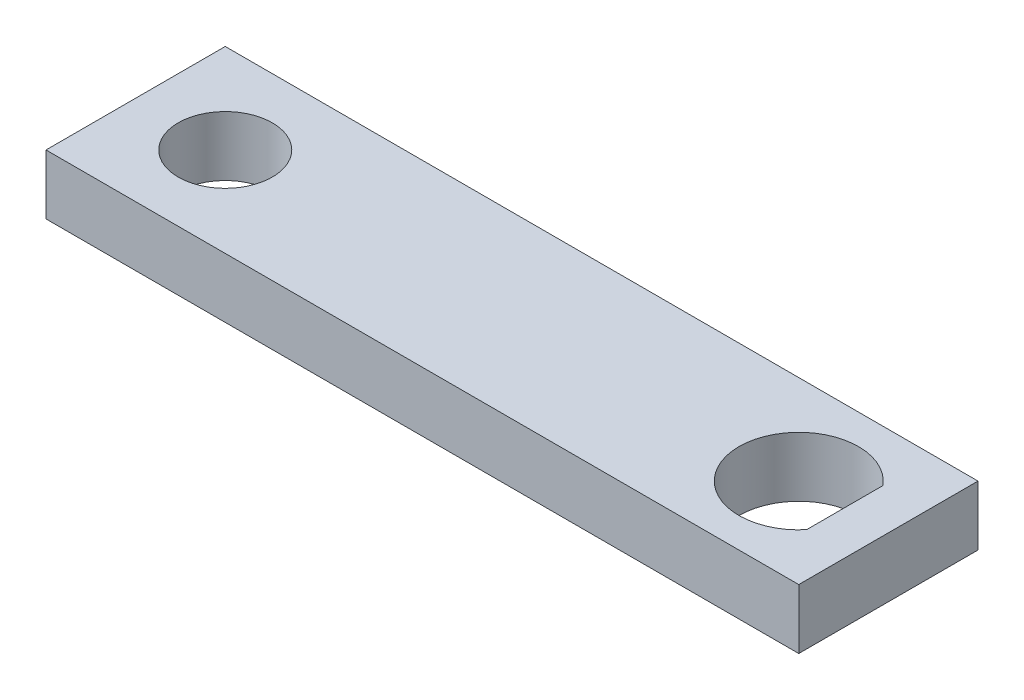
SolidWorks part; units mm, degrees
ref_plane "Front" through (0, 0, 0) normal (0, 0, 1) x (1, 0, 0)
ref_plane "Top" through (0, 0, 0) normal (0, 1, 0) x (-1, 0, 0)
ref_plane "Right" through (0, 0, 0) normal (1, 0, 0) x (0, 0, -1)
sketch "Sketch1" plane through (0, 0, 0) normal (0, 0, 1) x (1, 0, 0)
  line L0 (0, 0) -> (80, 0)
  line L1 (0, 0) -> (0, 6.35)
  line L2 (80, 6.35) -> (0, 6.35)
  line L3 (80, 6.35) -> (80, 0)
  dimension "D1" = 6.35
  dimension "D2" = 80
extrude "Base-Extrude" add sketch "Sketch1" along normal blind 19.05
sketch "Sketch2" plane through (0, 6.35, 0) normal (0, 1, 0) x (-1, 0, 0)
  line L0 (-80, 19.05) -> (-80, 0) construction
  line L1 (-80, 19.05) -> (0, 19.05) construction
  line L2 (-75.3645, 5.4734) -> (-75.3645, 13.5766)
  arc A0 (-75.3645, 5.4734) -> (-75.3645, 13.5766) centre (-70.475, 9.525) ccw
  dimension "D1" = 12.7
  dimension "D2" = 9.525
  dimension "D3" = 9.525
  dimension "D4" = 4.8895
extrude "Cut-Extrude1" cut sketch "Sketch2" against normal through all
sketch "Sketch3" plane through (0, 6.35, 0) normal (0, 1, 0) x (-1, 0, 0)
  line L0 (0, 19.05) -> (0, 0) construction
  circle A0 centre (-9.525, 9.525) radius 5
  arc A1 (-75.3645, 5.4734) -> (-75.3645, 13.5766) centre (-70.475, 9.525) ccw construction
  point P5 (-70.475, 9.525)
  dimension "D1" = 10
  dimension "D2" = 9.525
extrude "Cut-Extrude2" cut sketch "Sketch3" against normal through all
